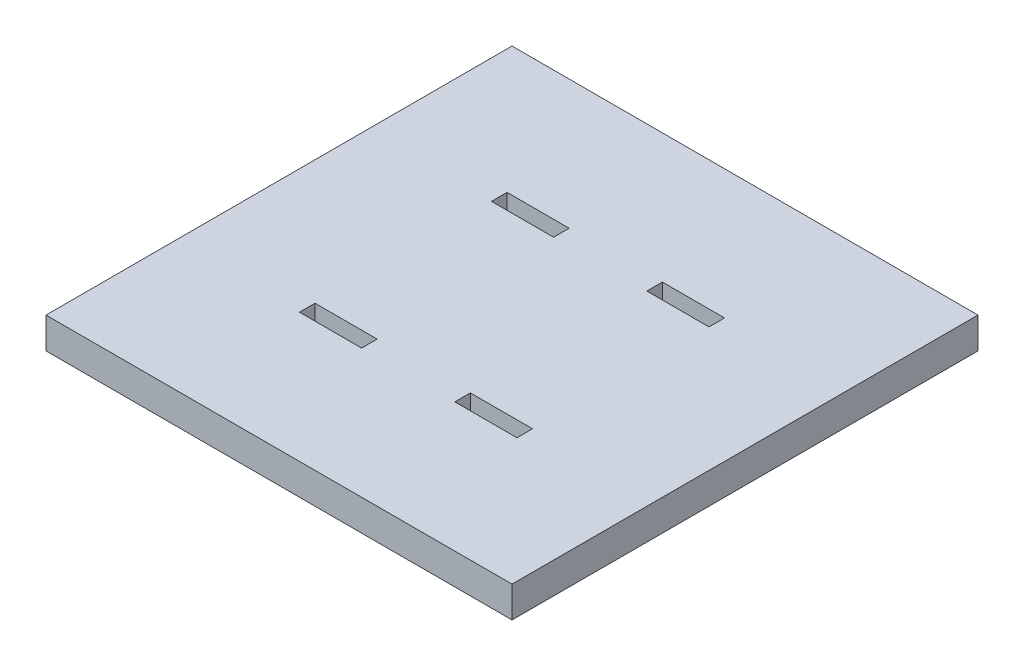
SolidWorks part; units mm, degrees
material "PPE"
ref_plane "Front Plane" through (0, 0, 0) normal (0, 0, 1) x (1, 0, 0)
ref_plane "Top Plane" through (0, 0, 0) normal (0, 1, 0) x (1, 0, 0)
ref_plane "Right Plane" through (0, 0, 0) normal (1, 0, 0) x (0, 0, -1)
sketch "Sketch15" plane through (0, 0, 0) normal (0, 1, 0) x (1, 0, 0)
  line L0 (0, 0) -> (75, 0) construction
  line L1 (75, -75) -> (-75, -75)
  line L2 (75, -75) -> (75, 75)
  line L3 (75, 75) -> (-75, 75)
  line L4 (-75, -75) -> (-75, 75)
  line L5 (75, -75) -> (-75, 75) construction
  line L6 (75, 75) -> (-75, -75) construction
  line L7 (-35, -28.4) -> (-15, -28.4)
  line L8 (-35, -28.4) -> (-35, -33.4)
  line L9 (-35, -33.4) -> (-15, -33.4)
  line L10 (-15, -28.4) -> (-15, -33.4)
  line L11 (15, -28.4) -> (35, -28.4)
  line L12 (15, -28.4) -> (15, -33.4)
  line L13 (15, -33.4) -> (35, -33.4)
  line L14 (35, -28.4) -> (35, -33.4)
  line L15 (15, 33.4) -> (35, 33.4)
  line L16 (35, 28.4) -> (35, 33.4)
  line L17 (15, 28.4) -> (35, 28.4)
  line L18 (15, 28.4) -> (15, 33.4)
  line L19 (-35, 33.4) -> (-15, 33.4)
  line L20 (-15, 28.4) -> (-15, 33.4)
  line L21 (-35, 28.4) -> (-15, 28.4)
  line L22 (-35, 28.4) -> (-35, 33.4)
  point P0 (0, 0)
  dimension "D1" = 150
  dimension "D2" = 150
  dimension "D3" = 5
  dimension "D4" = 20
  dimension "D5" = 30
  dimension "D6" = 15
  dimension "D7" = 28.4
extrude "Boss-Extrude1" add sketch "Sketch15" along normal mid plane 10
sketch "Sketch16" plane through (0, 0, 0) normal (0, 0, 1) x (1, 0, 0)
  line L0 (-75, 5) -> (75, 5) construction
  point P0 (0, 74.38)
  dimension "D1" = 69.38
move or copy body "Body-Move/Copy1" bodies to move or copy 115 copy no translate (0, -74.38, 0)
